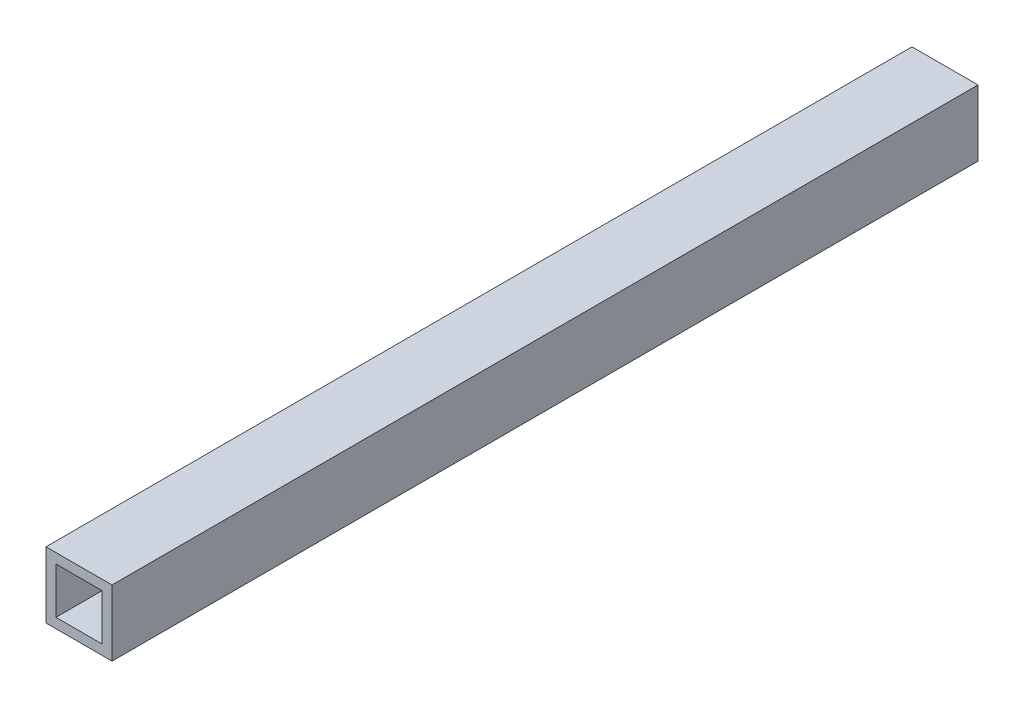
SolidWorks part; units mm, degrees
ref_plane "Front Plane" through (0, 0, 0) normal (0, 0, 1) x (1, 0, 0)
ref_plane "Top Plane" through (0, 0, 0) normal (0, 1, 0) x (1, 0, 0)
ref_plane "Right Plane" through (0, 0, 0) normal (1, 0, 0) x (0, 0, -1)
sketch "Sketch1" plane through (0, 0, 0) normal (0, 0, 1) x (1, 0, 0)
  line L1 (-5, 5) -> (5, 5)
  line L2 (-5, 5) -> (-5, -5)
  line L3 (-5, -5) -> (5, -5)
  line L4 (5, 5) -> (5, -5)
  line L5 (-5, 5) -> (5, -5) construction
  line L6 (-5, -5) -> (5, 5) construction
  line L7 (-3.5, -3.5) -> (3.5, -3.5)
  line L8 (-3.5, -3.5) -> (-3.5, 3.5)
  line L9 (-3.5, 3.5) -> (3.5, 3.5)
  line L10 (3.5, -3.5) -> (3.5, 3.5)
  line L11 (-3.5, -3.5) -> (3.5, 3.5) construction
  line L12 (-3.5, 3.5) -> (3.5, -3.5) construction
  point P0 (0, 0)
  point P6 (0, 0)
  dimension "D1" = 10
  dimension "D2" = 10
  dimension "D3" = 1.5
extrude "Boss-Extrude1" add sketch "Sketch1" along normal blind 131.16
